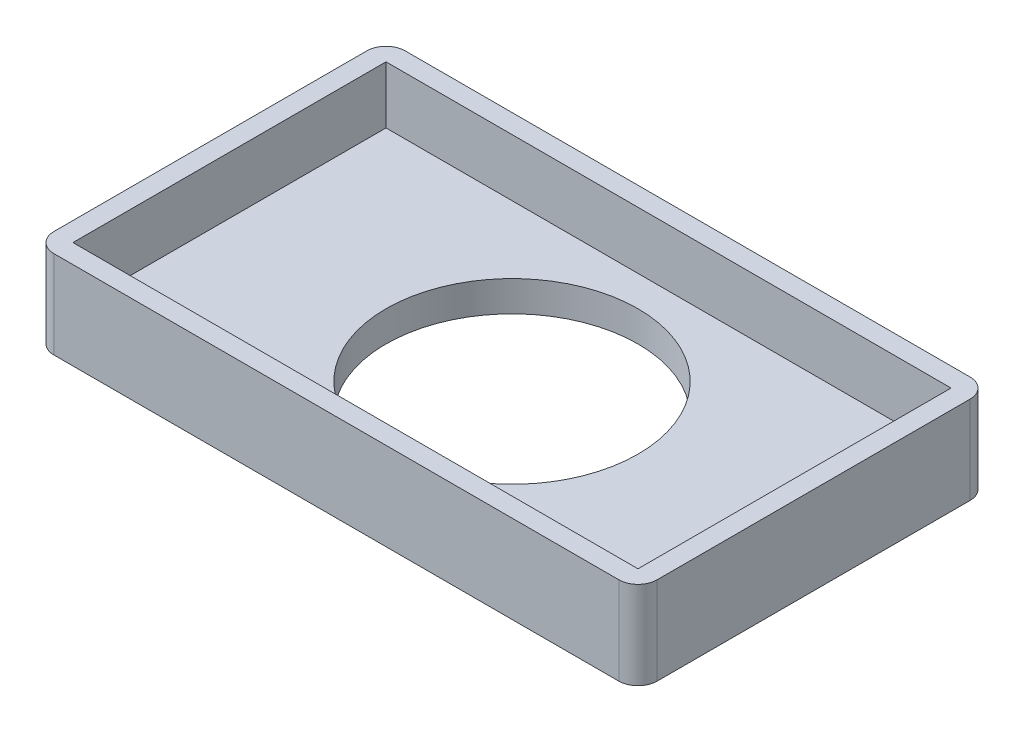
SolidWorks part; units mm, degrees
ref_plane "Front Plane" through (0, 0, 0) normal (0, 0, 1) x (1, 0, 0)
ref_plane "Top Plane" through (0, 0, 0) normal (0, 1, 0) x (1, 0, 0)
ref_plane "Right Plane" through (0, 0, 0) normal (1, 0, 0) x (0, 0, -1)
sketch "Sketch1" plane through (0, 0, 0) normal (0, 1, 0) x (1, 0, 0)
  line L1 (-79, 46) -> (79, 46)
  line L2 (-79, 46) -> (-79, -46)
  line L3 (-79, -46) -> (79, -46)
  line L4 (79, 46) -> (79, -46)
  line L5 (-79, 46) -> (79, -46) construction
  line L6 (-79, -46) -> (79, 46) construction
  point P0 (0, 0)
  dimension "D1" = 158
  dimension "D2" = 92
extrude "Boss-Extrude1" add sketch "Sketch1" along normal blind 8
sketch "Sketch2" plane through (0, 8, 0) normal (0, 1, 0) x (1, 0, 0)
  line L1 (-74, 41) -> (74, 41)
  line L2 (-74, 41) -> (-74, -41)
  line L3 (-74, -41) -> (74, -41)
  line L4 (74, 41) -> (74, -41)
  line L5 (-74, 41) -> (74, -41) construction
  line L6 (-74, -41) -> (74, 41) construction
  line L7 (-79, 46) -> (79, 46)
  line L8 (-79, 46) -> (-79, -46)
  line L9 (-79, -46) -> (79, -46)
  line L10 (79, 46) -> (79, -46)
  line L11 (-79, 46) -> (79, -46) construction
  line L12 (-79, -46) -> (79, 46) construction
  point P0 (0, 0)
  point P6 (0, 0)
  dimension "D1" = 148
  dimension "D2" = 82
extrude "Boss-Extrude2" add sketch "Sketch2" along normal blind 15
sketch "Sketch3" plane through (0, 0, 0) normal (0, -1, 0) x (1, 0, 0)
  circle A0 centre (0, 0) radius 33
  dimension "D1" = 66
extrude "Cut-Extrude1" cut sketch "Sketch3" against normal through all
fillet "Fillet1" radius 5 1 edges at (-79, 11.5, 46)
fillet "Fillet2" radius 5 3 edges at (79, 11.5, 46) (79, 11.5, -46) (-79, 11.5, -46)
sketch "Sketch4" plane through (0, 23, 0) normal (0, 1, 0) x (1, 0, 0)
  line L1 (-29, 41) -> (-29, 46)
  line L2 (74, 41) -> (-74, 41) construction
  line L3 (74, 46) -> (-74, 46) construction
  line L4 (-29, 46) -> (-29, 41)
  line L5 (54, 41) -> (54, 46)
  line L6 (54, 46) -> (54, 41)
  line L7 (-79, 41) -> (-79, -41) construction
  line L8 (79, -41) -> (79, 41) construction
  dimension "D1" = 50
  dimension "D2" = 25
sketch "Sketch5" plane through (0, 0, -46) normal (0, 0, -1) x (-1, 0, 0)
  line L0 (-54, 23) -> (-54, 0)
  line L1 (-74, 0) -> (74, 0) construction
  line L2 (29, 23) -> (29, 0)
